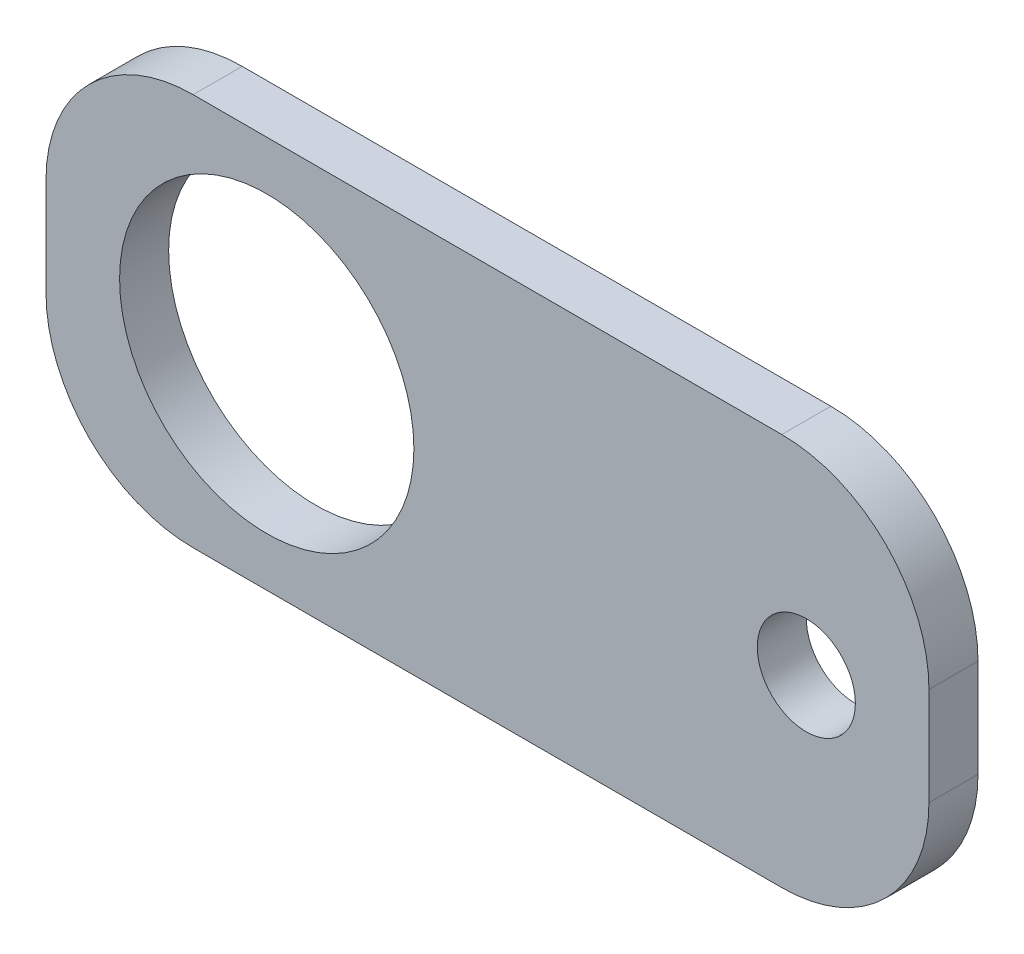
SolidWorks part; units mm, degrees
ref_plane "Front Plane" through (0, 0, 0) normal (1, 0, 0) x (0, 1, 0)
ref_plane "Top Plane" through (0, 0, 0) normal (0, 0, 1) x (0, 1, 0)
ref_plane "Right Plane" through (0, 0, 0) normal (0, 1, 0) x (-1, 0, 0)
sketch "Sketch1" plane through (0, 0, 0) normal (0, 0, 1) x (0, 1, 0)
  line L1 (0, 0) -> (8, 0)
  line L2 (0, 0) -> (0, -18)
  line L3 (0, -18) -> (8, -18)
  line L4 (8, 0) -> (8, -18)
  circle A0 centre (4, -15.5) radius 1
  circle A1 centre (4, -4.5) radius 3
  dimension "D7" = 6
  dimension "D8" = 2
  dimension "D1" = 18
  dimension "D2" = 8
  dimension "D3" = 11
  dimension "D4" = 2.5
  dimension "D5" = 4
  dimension "D6" = 4
extrude "Boss-Extrude1" add sketch "Sketch1" along normal blind 1
fillet "Fillet1" radius 3 4 edges at (18, 0, 0.5) (0, 0, 0.5) (0, 8, 0.5) (18, 8, 0.5)
